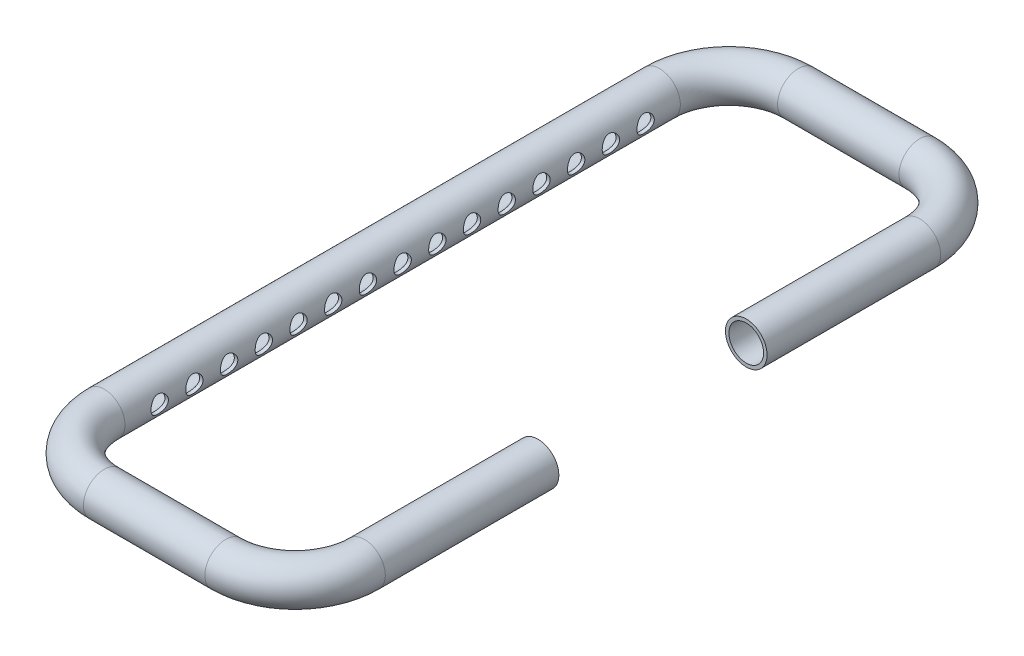
SolidWorks part; units mm, degrees
material "Custom Plastic"
ref_plane "Ön Düzlem" through (0, 0, 0) normal (1, 0, 0) x (0, 1, 0)
ref_plane "Üst Düzlem" through (0, 0, 0) normal (0, 0, 1) x (0, 1, 0)
ref_plane "Sağ Düzlem" through (0, 0, 0) normal (0, 1, 0) x (-1, 0, 0)
sketch "Sketch4" plane through (0, 0, 0) normal (0, 0, 1) x (0, 1, 0)
  circle A0 centre (0, 0) radius 5
  circle A1 centre (0, 0) radius 6
sketch "Sketch5" plane through (0, 0, 0) normal (0, 1, 0) x (-1, 0, 0)
  line L0 (0, 0) -> (0, 60) construction
  line L1 (5, 0) -> (-5, 0) construction
  line L2 (0, 0) -> (0, -50)
  line L3 (75, -50) -> (75, 110)
  line L4 (20, -70) -> (55, -70)
  line L8 (55, 130) -> (20, 130)
  line L9 (0, 110) -> (0, 60)
  arc A1 (0, -50) -> (20, -70) centre (20, -50) ccw
  arc A2 (55, -70) -> (75, -50) centre (55, -50) ccw
  arc A3 (75, 110) -> (55, 130) centre (55, 110) ccw
  arc A4 (20, 130) -> (0, 110) centre (20, 110) ccw
sweep "Sweep1" add profiles "Sketch4" path "Sketch5"
ref_plane "Plane1" through (-6, 0, 0) normal (1, 0, 0) x (0, 0, -1)
ref_plane "Plane2" through (-86, 0, 0) normal (1, 0, 0) x (0, 0, -1)
sketch "Sketch7" plane through (-86, 0, 0) normal (1, 0, 0) x (0, 0, -1)
  line L0 (50, 0) -> (40, 0) construction
  line L1 (50, 6) -> (50, -6) construction
  line L2 (-110, 0) -> (-100, 0) construction
  line L3 (-110, 6) -> (-110, -6) construction
  circle A0 centre (-100, 0) radius 2.5
  circle A1 centre (-90, 0) radius 2.5
  circle A2 centre (-80, 0) radius 2.5
  circle A3 centre (-70, 0) radius 2.5
  circle A4 centre (-60, 0) radius 2.5
  circle A5 centre (-50, 0) radius 2.5
  circle A6 centre (-40, 0) radius 2.5
  circle A7 centre (-30, 0) radius 2.5
  circle A8 centre (-20, 0) radius 2.5
  circle A9 centre (-10, 0) radius 2.5
  circle A10 centre (0, 0) radius 2.5
  circle A11 centre (10, 0) radius 2.5
  circle A12 centre (20, 0) radius 2.5
  circle A13 centre (30, 0) radius 2.5
  circle A14 centre (40, 0) radius 2.5
  dimension "D1" = 15
extrude "Cut-Extrude1" cut sketch "Sketch7" along normal blind 25
